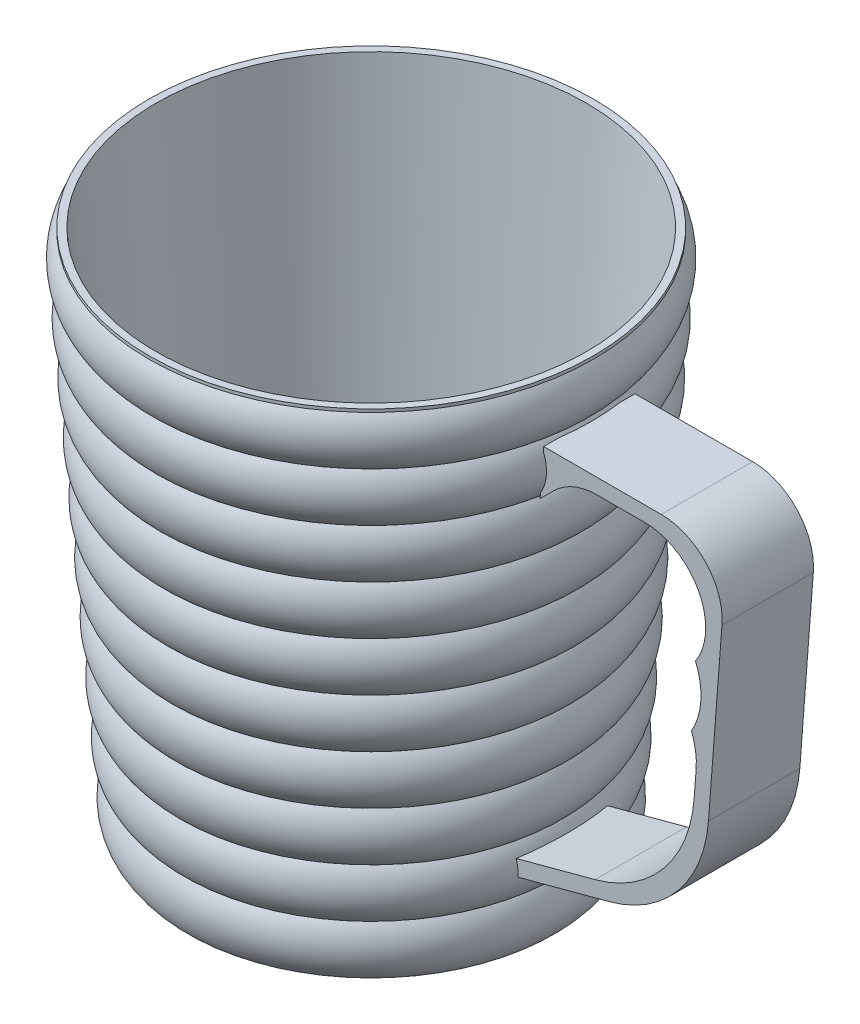
SolidWorks part; units mm, degrees
ref_plane "Front Plane" through (0, 0, 0) normal (0, 0, 1) x (1, 0, 0)
ref_plane "Top Plane" through (0, 0, 0) normal (0, 1, 0) x (1, 0, 0)
ref_plane "Right Plane" through (0, 0, 0) normal (1, 0, 0) x (0, 0, -1)
sketch "Sketch1" plane through (0, 0, 0) normal (0, 0, 1) x (1, 0, 0)
  line L0 (0, 0) -> (0, 93.8755) construction
  line L1 (0, 85) -> (36.5, 85)
  line L2 (36.5, 85) -> (30, 0)
  line L3 (30, 0) -> (27, 0)
  line L4 (27, 0) -> (27, 1)
  line L5 (0, 2.8) -> (-26.2035, 2.8) construction
  line L6 (0, 85) -> (0, 2.8)
  arc A0 (0, 2.8) -> (27, 1) centre (0, -200.6) cw
  point P10 (0, 93.8755)
  dimension "D1" = 60
  dimension "D2" = 73
  dimension "D3" = 3
  dimension "D4" = 1
  dimension "D5" = 2.8
  dimension "D6" = 85
revolve "Revolve1" add sketch "Sketch1" angle 360 about L0
sketch "Sketch2" plane through (0, 0, 0) normal (0, 0, 1) x (1, 0, 0)
  line L0 (30, 0) -> (36.5, 85) construction
  line L1 (30, 0) -> (36.5, 85)
  line L2 (31.4956, -0.1144) -> (37.9956, 84.8856) construction
  line L3 (0, 0) -> (0, 97.2045) construction
  arc A0 (30.65, 8.5) -> (30, 0) centre (25.0344, 4.6546) cw
  arc A1 (31.3, 17) -> (30.65, 8.5) centre (25.6844, 13.1546) cw
  arc A2 (31.95, 25.5) -> (31.3, 17) centre (26.3344, 21.6546) cw
  arc A3 (32.6, 34) -> (31.95, 25.5) centre (26.9844, 30.1546) cw
  arc A4 (33.25, 42.5) -> (32.6, 34) centre (27.6344, 38.6546) cw
  arc A5 (33.9, 51) -> (33.25, 42.5) centre (28.2844, 47.1546) cw
  arc A6 (35.2, 68) -> (34.55, 59.5) centre (29.5844, 64.1546) cw
  arc A7 (36.5, 85) -> (35.85, 76.5) centre (30.8844, 81.1546) cw
  arc A8 (35.2, 68) -> (35.85, 76.5) centre (30.2344, 72.6546) ccw
  arc A9 (34.55, 59.5) -> (33.9, 51) centre (28.9344, 55.6546) cw
  point P4 (30.65, 8.5)
  point P5 (31.3, 17)
  point P6 (31.95, 25.5)
  point P7 (32.6, 34)
  point P8 (33.25, 42.5)
  point P9 (33.9, 51)
  point P10 (34.55, 59.5)
  point P11 (35.2, 68)
  point P12 (35.85, 76.5)
  dimension "D1" = 1.5
revolve "Revolve2" add sketch "Sketch2" angle 360 about L3
sketch "Sketch3" plane through (0, 0, 0) normal (0, 0, 1) x (1, 0, 0)
  line L0 (30, 0) -> (36.5, 85) construction
  line L1 (30.9559, 12.5) -> (31.1579, 15.1423)
  line L2 (65.0763, 65.2375) -> (62.8612, 36.2699)
  line L3 (35.8118, 76) -> (55.1055, 76)
  line L4 (30.9559, 12.5) -> (46.6192, 16.697)
  line L5 (35.2229, 68.3) -> (37.494, 70.5711)
  line L6 (44.5651, 73.5) -> (52.407, 73.5)
  line L7 (60.8397, 42.6231) -> (60.5035, 38.2263)
  line L8 (44.2615, 18.6534) -> (31.1579, 15.1423)
  line L9 (62.407, 63.1188) -> (61.6044, 52.6231) construction
  line L10 (61.6044, 52.6231) -> (60.8397, 42.6231) construction
  line L11 (35.8118, 76) -> (36.5, 85) construction
  line L12 (31.1579, 15.1423) -> (35.2229, 68.3) construction
  line L13 (35.2229, 68.3) -> (35.8118, 76)
  line L14 (30, 0) -> (30.9559, 12.5) construction
  arc A0 (65.0763, 65.2375) -> (55.1055, 76) centre (55.1055, 66) ccw
  arc A1 (52.407, 73.5) -> (60.7356, 57.9652) centre (52.407, 63.5) cw
  arc A2 (62.8612, 36.2699) -> (46.6192, 16.697) centre (40.9252, 37.9474) cw
  arc A3 (60.5035, 38.2263) -> (44.2615, 18.6534) centre (38.5675, 39.9038) cw
  arc A4 (60.0745, 47.7109) -> (60.7356, 57.9652) centre (50.1379, 53.5) ccw
  arc A5 (60.8397, 42.6231) -> (60.0745, 47.7109) centre (49.3732, 43.5) ccw
  arc A6 (60.7356, 57.9652) -> (39.4366, 49.2891) centre (50.1379, 53.5) ccw construction
  arc A7 (60.7356, 57.9652) -> (54.6002, 53.7435) centre (52.407, 63.5) cw construction
  arc A8 (47.4191, 54.8328) -> (52.407, 73.5) centre (52.407, 63.5) cw construction
  arc A9 (60.0745, 47.7109) -> (54.6002, 53.7435) centre (49.3732, 43.5) ccw construction
  arc A10 (54.6002, 53.7435) -> (47.4191, 54.8328) centre (52.407, 63.5) cw construction
  arc A11 (54.6002, 53.7435) -> (47.4191, 54.8328) centre (49.3732, 43.5) ccw construction
  arc A12 (47.4191, 54.8328) -> (39.4366, 49.2891) centre (49.3732, 43.5) ccw construction
  arc A13 (39.4366, 49.2891) -> (60.0745, 47.7109) centre (50.1379, 53.5) ccw construction
  arc A14 (39.4366, 49.2891) -> (60.8397, 42.6231) centre (49.3732, 43.5) ccw construction
  arc A15 (37.494, 70.5711) -> (44.5651, 73.5) centre (44.5651, 63.5) cw
  point P11 (56.0087, 45.0237)
  point P20 (0, 0)
  point P25 (0, 0)
  point P26 (56.0734, 45.8698)
  point P33 (0, 0)
  dimension "D10" = 10
  dimension "D11" = 22
  dimension "D12" = 23
  dimension "D15" = 10
  dimension "D16" = 10
  dimension "D1" = 30
  dimension "D2" = 9
  dimension "D3" = 12.5
  dimension "D4" = 15
  dimension "D5" = 7.7
  dimension "D6" = 2.5
  dimension "D7" = 2.5
  dimension "D8" = 2.5
  dimension "D9" = 135
  dimension "D13" = 20
  dimension "D14" = 10
extrude "Boss-Extrude1" add sketch "Sketch3" along normal mid plane 15
sketch "Sketch4" plane through (0, 0, 0) normal (0, 0, 1) x (1, 0, 0)
  line L0 (35.2965, 85) -> (29.1024, 4)
  line L1 (36.5, 85) -> (-36.5, 85) construction
  line L2 (29.1024, 4) -> (0, 4)
  line L3 (0, 0) -> (0, 91.8941) construction
  line L4 (36.5, 85) -> (30, 0) construction
  line L5 (35.2965, 85) -> (0, 85)
  line L6 (0, 85) -> (0, 4)
  dimension "D1" = 4
  dimension "D2" = 1.2
revolve "Cut-Revolve1" cut sketch "Sketch4" angle 360 about L3
sketch "Sketch5" plane through (0, 0, 0) normal (0, 0, 1) x (1, 0, 0)
  line L0 (36.5, 85) -> (-36.5, 85) construction
  line L1 (35.2965, 85) -> (36.5, 85)
  line L2 (35.2965, 85) -> (35.3347, 85.5)
  line L3 (35.3347, 85.5) -> (36.5, 85.5)
  line L4 (36.5, 85) -> (36.5, 85.5)
  line L5 (36.5, 85) -> (-36.5, 85) construction
  line L6 (0, 0) -> (0, 93.1644) construction
  line L7 (29.1024, 4) -> (35.2965, 85) construction
  dimension "D1" = 0.5
revolve "Revolve3" add sketch "Sketch5" angle 360 about L6
